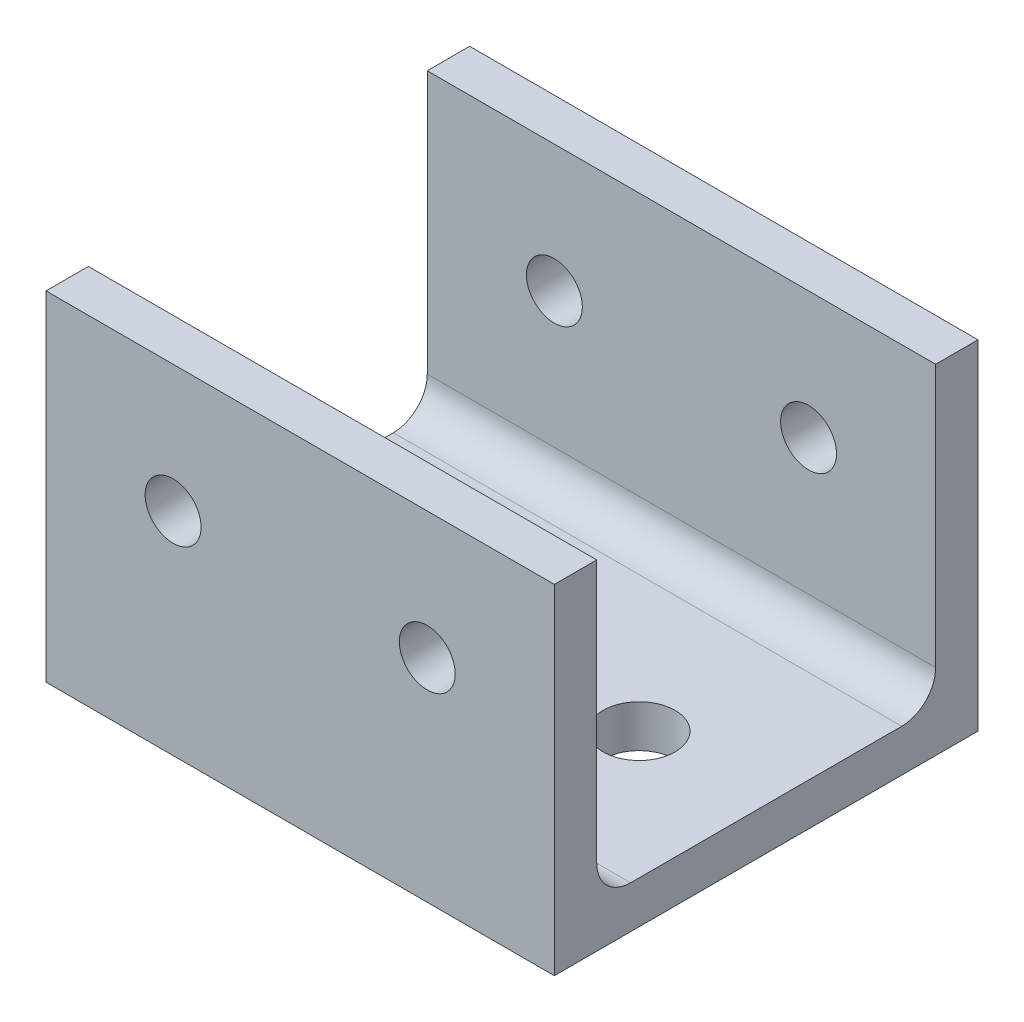
SolidWorks part; units mm, degrees
ref_plane "前基準面" through (0, 0, 0) normal (0, 0, 1) x (1, 0, 0)
ref_plane "上基準面" through (0, 0, 0) normal (0, 1, 0) x (1, 0, 0)
ref_plane "右基準面" through (0, 0, 0) normal (1, 0, 0) x (0, 0, -1)
sketch "草圖1" plane through (0, 0, 0) normal (1, 0, 0) x (0, 0, -1)
  line L0 (0, 0) -> (50, 0)
  line L1 (50, 0) -> (50, 40)
  line L2 (50, 40) -> (45, 40)
  line L3 (45, 40) -> (45, 5)
  line L4 (45, 5) -> (5, 5)
  line L5 (5, 5) -> (5, 40)
  line L6 (5, 40) -> (0, 40)
  line L7 (0, 40) -> (0, 0)
extrude "填料-伸長1" add sketch "草圖1" along normal blind 60
sketch "草圖2" plane through (0, 0, 0) normal (0, 1, 0) x (1, 0, 0)
  circle A0 centre (15, 25) radius 4.25
  circle A1 centre (45, 25) radius 4.25
extrude "除料-伸長1" cut sketch "草圖2" along normal through all
sketch "草圖3" plane through (0, 0, 0) normal (0, 0, 1) x (1, 0, 0)
  circle A0 centre (15, 25) radius 3.3
  circle A1 centre (45, 25) radius 3.3
extrude "除料-伸長2" cut sketch "草圖3" against normal through all
fillet "圓角1" radius 4 2 edges at (30, 5, -5) (30, 5, -45)
